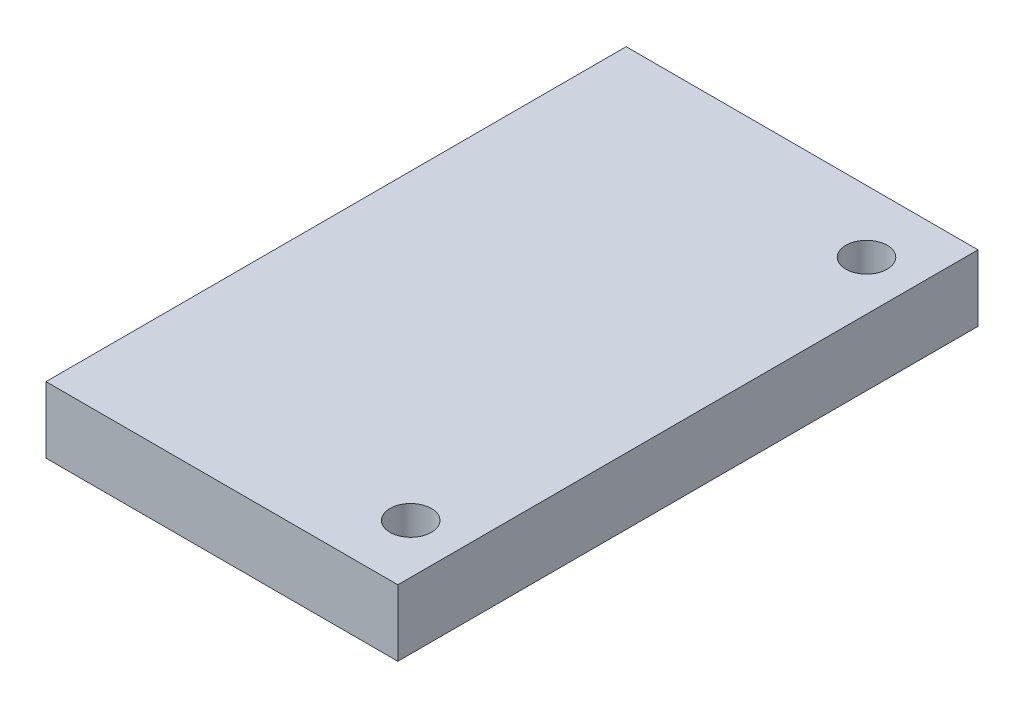
SolidWorks part; units mm, degrees
ref_plane "Спереди" through (0, 0, 0) normal (0, 0, 1) x (1, 0, 0)
ref_plane "Сверху" through (0, 0, 0) normal (0, 1, 0) x (1, 0, 0)
ref_plane "Справа" through (0, 0, 0) normal (1, 0, 0) x (0, 0, -1)
sketch "Эскиз1" plane through (0, 0, 0) normal (0, 1, 0) x (1, 0, 0)
  line L1 (-8.5, 7) -> (-0.0095, 7)
  line L2 (-8.5, 7) -> (-8.5, -7)
  line L3 (-8.5, -7) -> (-0.0095, -7)
  line L5 (-8.5, 7) -> (0, 0) construction
  line L6 (-8.5, -7) -> (0, 0) construction
  line L10 (-1.2, 5.5) -> (-1.2, -5.5) construction
  line L11 (-1.2, 0) -> (0, 0) construction
  line L12 (-0.0095, 7) -> (-0.0095, -7)
  circle A7 centre (-1.2, 5.5) radius 0.5
  circle A8 centre (-1.2, -5.5) radius 0.5
  point P0 (0, 0)
  point P26 (-1.2, 0)
  point P29 (0, 0)
  dimension "D10" = 1
  dimension "D1" = 14
  dimension "D11" = 11
extrude "Бобышка-Вытянуть1" add sketch "Эскиз1" along normal blind 1.6
